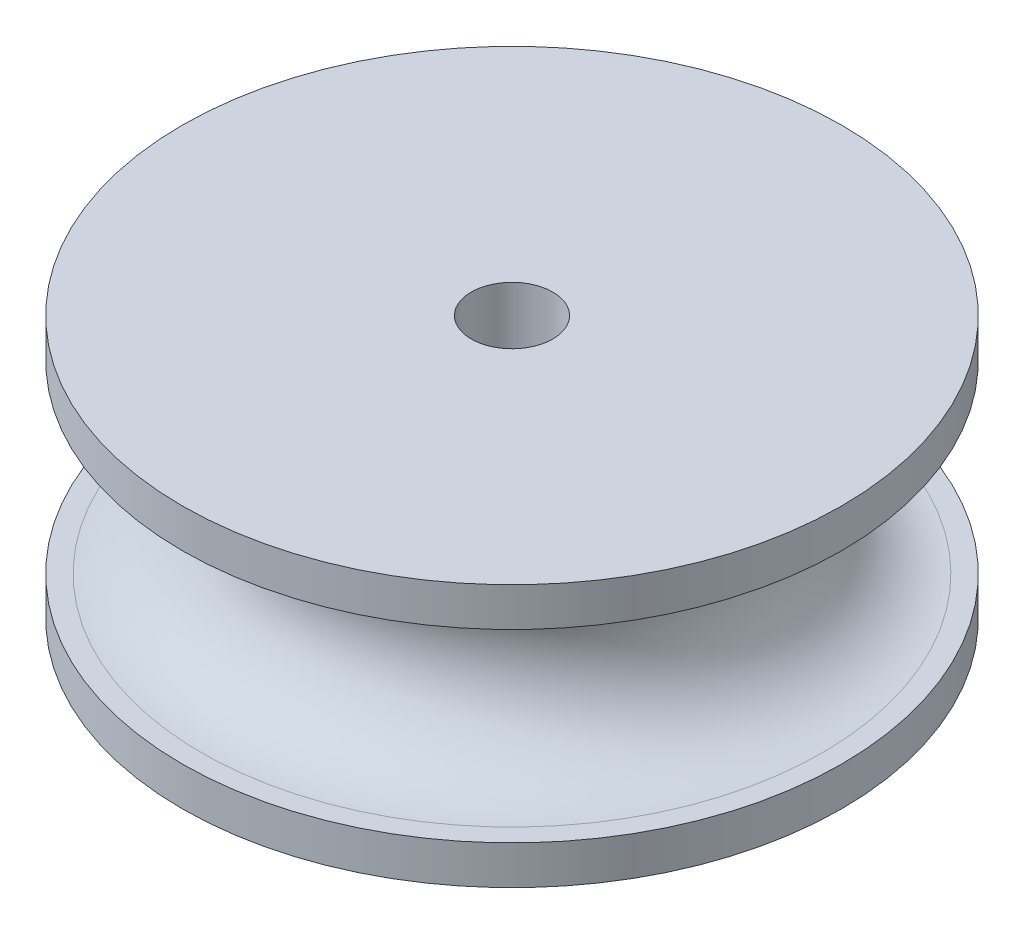
SolidWorks part; units mm, degrees
material "ABS PC"
ref_plane "Front Plane" through (0, 0, 0) normal (0, 0, 1) x (1, 0, 0)
ref_plane "Top Plane" through (0, 0, 0) normal (0, 1, 0) x (1, 0, 0)
ref_plane "Right Plane" through (0, 0, 0) normal (1, 0, 0) x (0, 0, -1)
sketch "Sketch1" plane through (0, 0, 0) normal (0, 0, 1) x (1, 0, 0)
  line L0 (-1.05, 0) -> (-1.05, 6.7625)
  line L3 (-1.05, 6.7625) -> (-8.5, 6.7625)
  line L4 (-8.5, 6.7625) -> (-8.5, 5.7625)
  line L5 (-8.5, 5.7625) -> (-8, 5.7625)
  line L6 (-8, 1) -> (-8.5, 1)
  line L7 (-8.5, 1) -> (-8.5, 0)
  line L8 (-8.5, 0) -> (-1.05, 0)
  line L9 (0, 0) -> (0, 22.8832) construction
  arc A0 (-8, 5.7625) -> (-8, 1) centre (-8, 3.3813) cw
  point P4 (-1, 9)
  point P9 (-1, 6.7625)
  point P15 (-1.0817, 6.7625)
  dimension "D1" = 8
  dimension "D4" = 2.3813
  dimension "D3" = 1
  dimension "D5" = 0.5
  dimension "D6" = 1.05
revolve "Revolve1" add sketch "Sketch1" angle 360 about L9
